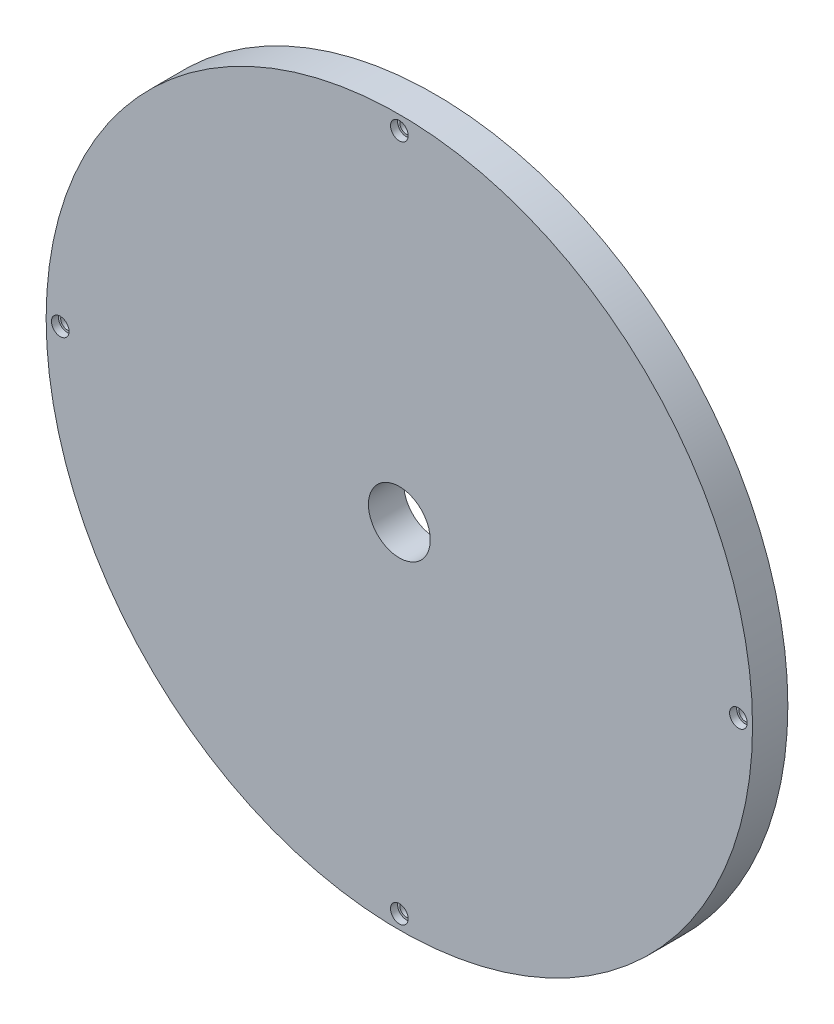
SolidWorks part; units mm, degrees
ref_plane "Front Plane" through (0, 0, 0) normal (0, 0, 1) x (1, 0, 0)
ref_plane "Top Plane" through (0, 0, 0) normal (0, 1, 0) x (1, 0, 0)
ref_plane "Right Plane" through (0, 0, 0) normal (1, 0, 0) x (0, 0, -1)
sketch "Sketch1" plane through (0, 0, 0) normal (0, 0, 1) x (1, 0, 0)
  circle A0 centre (0, 0) radius 63.5
extrude "Boss-Extrude1" add sketch "Sketch1" along normal blind 6.35
sketch "Sketch2" plane through (0, 0, 0) normal (0, 0, -1) x (-1, 0, 0)
  circle A0 centre (0, 0) radius 50.8
  circle A1 centre (0, 0) radius 57.15
extrude "Cut-Extrude1" cut sketch "Sketch2" against normal blind 1.27
sketch "Sketch4" plane through (0, 0, 0) normal (0, 0, -1) x (-1, 0, 0)
  circle A0 centre (0, 60.96) radius 1.1906
  circle A1 centre (60.96, 0) radius 1.1906
  circle A2 centre (0, -60.96) radius 1.1906
  circle A3 centre (-60.96, 0) radius 1.1906
  point P12 (0, 0)
  dimension "D1" = 60.96
  dimension "D2" = 4
extrude "Cut-Extrude2" cut sketch "Sketch4" against normal through all
sketch "Sketch5" plane through (0, 0, 6.35) normal (0, 0, 1) x (1, 0, 0)
  circle A0 centre (0, 60.96) radius 1.5875
  circle A1 centre (60.96, 0) radius 1.5875
  circle A2 centre (0, -60.96) radius 1.5875
  circle A3 centre (-60.96, 0) radius 1.5875
  point P12 (0, 0)
  dimension "D1" = 4
extrude "Cut-Extrude3" cut sketch "Sketch5" against normal blind 1.27
sketch "Sketch6" plane through (0, 0, 0) normal (0, 0, -1) x (-1, 0, 0)
  circle A0 centre (0, 0) radius 5.5562
extrude "Cut-Extrude4" cut sketch "Sketch6" against normal through all
